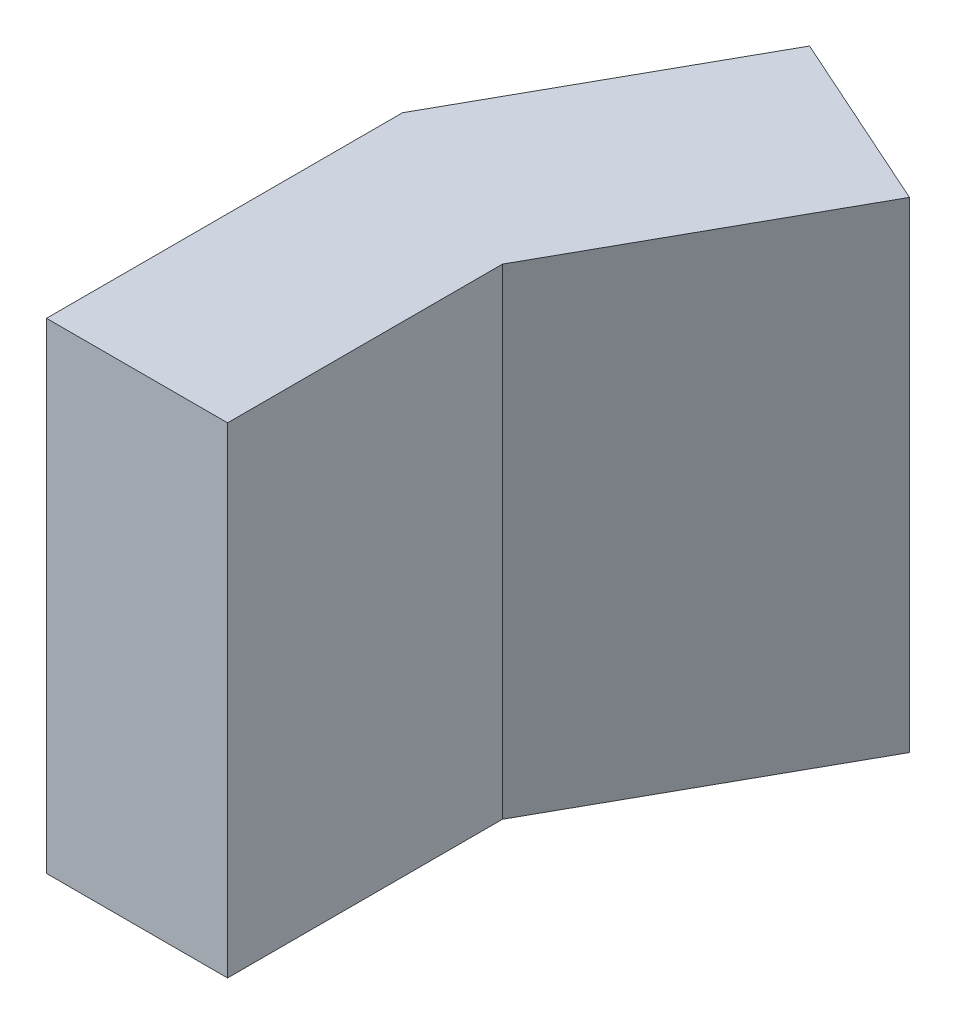
SolidWorks part; units mm, degrees
ref_plane "Front Plane" through (0, 0, 0) normal (0, 0, 1) x (1, 0, 0)
ref_plane "Top Plane" through (0, 0, 0) normal (0, 1, 0) x (1, 0, 0)
ref_plane "Right Plane" through (0, 0, 0) normal (1, 0, 0) x (0, 0, -1)
sketch "Sketch1" plane through (0, 0, 0) normal (0, 1, 0) x (1, 0, 0)
  line L0 (0, 32.246) -> (0, -11.0171)
  line L1 (11, -11.0171) -> (-11, -11.0171)
  line L2 (11, -11.0171) -> (11, 32.246)
  line L3 (11, 32.246) -> (-11, 32.246)
  line L4 (-11, -11.0171) -> (-11, 32.246)
  line L5 (-11, 32.246) -> (11, 22.3873)
  line L6 (-11, 32.246) -> (6.7066, 63.996)
  line L7 (11, 22.3873) -> (28.7066, 54.1373)
  line L8 (6.7066, 63.996) -> (28.7066, 54.1373)
  circle A0 centre (0, 0) radius 4.2724
  circle A1 centre (0, 20.1) radius 4.3133
  dimension "D1" = 20.1
  dimension "D2" = 22
  dimension "D3" = 31.75
extrude "Boss-Extrude1" add sketch "Sketch1" along normal blind 58.42 contours L8 L6 L3 L2 L7 | L0 L5 L2 L3 | A1 L0 A0 L1 L2 L5 | L3 L5 L0 | A1 L0 L5 L4 L1 A0 | L0 A1 | L0 A0 | L0 A0 | L0 A1
